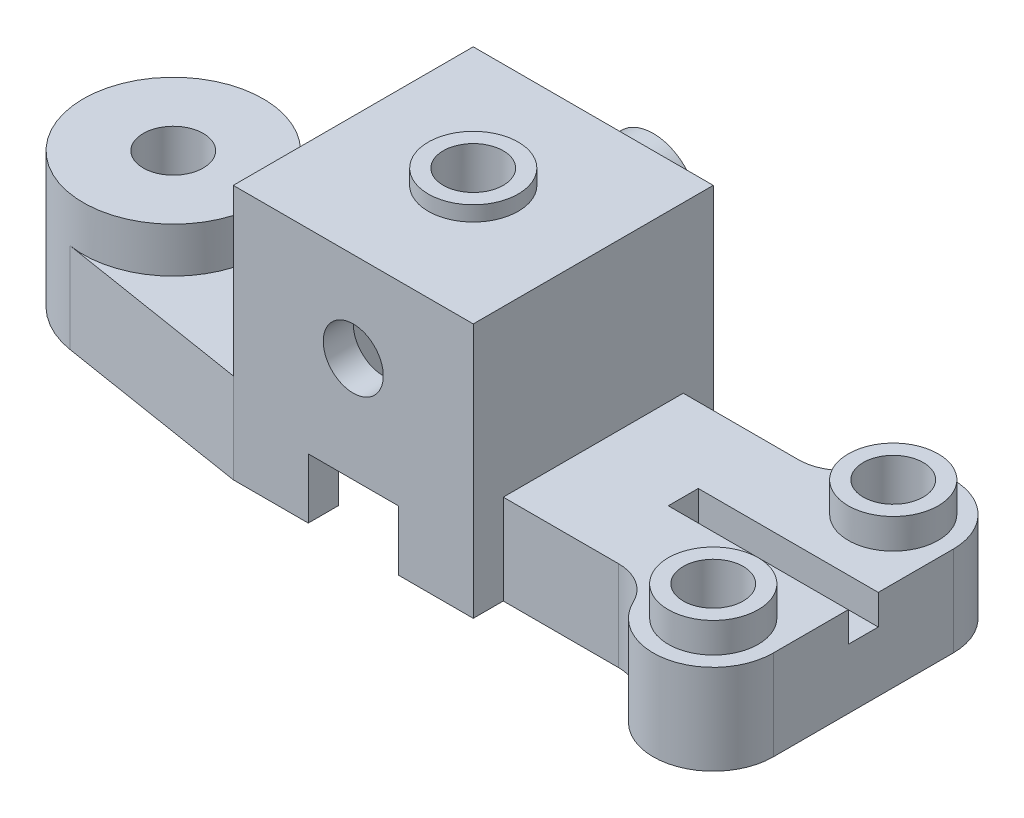
SolidWorks part; units mm, degrees
ref_plane "Front Plane" through (0, 0, 0) normal (0, 0, 1) x (1, 0, 0)
ref_plane "Top Plane" through (0, 0, 0) normal (0, 1, 0) x (1, 0, 0)
ref_plane "Right Plane" through (0, 0, 0) normal (1, 0, 0) x (0, 0, -1)
sketch "Sketch2" plane through (0, 0, 0) normal (0, 1, 0) x (1, 0, 0)
  line L1 (-40, -40) -> (40, -40)
  line L2 (-40, -40) -> (-40, 40)
  line L3 (-40, 40) -> (40, 40)
  line L4 (40, -40) -> (40, 40)
  line L5 (-40, -40) -> (40, 40) construction
  line L6 (-40, 40) -> (40, -40) construction
  point P0 (0, 0)
  dimension "D1" = 80
  dimension "D2" = 80
extrude "Boss-Extrude1" add sketch "Sketch2" along normal blind 85
sketch "Sketch3" plane through (0, 0, 40) normal (0, 0, 1) x (1, 0, 0)
  line L1 (15, -20) -> (-15, -20)
  line L2 (15, -20) -> (15, 20)
  line L3 (15, 20) -> (-15, 20)
  line L4 (-15, -20) -> (-15, 20)
  line L5 (15, -20) -> (-15, 20) construction
  line L6 (15, 20) -> (-15, -20) construction
  line L7 (-40, 0) -> (40, 0) construction
  dimension "D1" = 30
  dimension "D2" = 20
extrude "Cut-Extrude1" cut sketch "Sketch3" against normal through all
sketch "Sketch4" plane through (0, 0, -40) normal (0, 0, -1) x (-1, 0, 0)
  line L0 (15, 0) -> (40, 0) construction
  circle A0 centre (0, 55) radius 15
  point P1 (-5.7798, 40.8579)
  point P6 (0, 0)
  point P12 (0, 0)
  dimension "D1" = 30
  dimension "D2" = 55
extrude "Boss-Extrude2" add sketch "Sketch4" along normal blind 20
sketch "Sketch5" plane through (0, 85, 0) normal (0, 1, 0) x (1, 0, 0)
  circle A0 centre (0, 0) radius 15
  dimension "D1" = 30
extrude "Boss-Extrude3" add sketch "Sketch5" along normal blind 5
sketch "Sketch7" plane through (0, 0, 0) normal (0, 1, 0) x (1, 0, 0)
  circle A0 centre (-100, 0) radius 30
  circle A1 centre (0, 0) radius 15 construction
  point P4 (0, 0)
  dimension "D1" = 60
  dimension "D2" = 100
extrude "Boss-Extrude4" add sketch "Sketch7" along normal blind 45 separate body
sketch "Sketch9" plane through (0, 0, 0) normal (0, 1, 0) x (1, 0, 0)
  line L0 (-40, 40) -> (-104.7479, 29.6219)
  line L1 (0, 0) -> (-100, 0) construction
  line L2 (-40, -40) -> (-104.7479, -29.6219)
  line L3 (-40, 40) -> (-40, -40) construction
  line L4 (-40, 40) -> (-40, -40)
  circle A0 centre (-100, 0) radius 30 construction
  circle A1 centre (-100, 0) radius 30
extrude "Boss-Extrude5" add sketch "Sketch9" along normal blind 30 contours L1 L4 L0 A1 | L4 L1 A1 L2
sketch "Sketch10" plane through (0, 0, 0) normal (0, -1, 0) x (1, 0, 0)
  line L0 (-50, 28.2695) -> (-50, -28.2695)
  line L6 (-50, 28.2695) -> (-103.1653, 19.7479)
  line L7 (-40, 40) -> (-104.7479, 29.6219) construction
  line L8 (-50, -28.2695) -> (-103.1653, -19.7479)
  line L9 (-40, -40) -> (-104.7479, -29.6219) construction
  arc A0 (-104.7479, 29.6219) -> (-104.7479, -29.6219) centre (-100, 0) ccw construction
  arc A1 (-104.7479, 29.6219) -> (-104.7479, -29.6219) centre (-100, 0) ccw
  arc A2 (-103.1653, 19.7479) -> (-103.1653, -19.7479) centre (-100, 0) ccw
  point P2 (-50.4641, 28.1951)
  point P8 (0, 0)
  point P16 (0, 0)
  point P17 (0, 0)
  dimension "D4" = 20
  dimension "D1" = 10
  dimension "D2" = 10
  dimension "D3" = 10
extrude "Cut-Extrude2" cut sketch "Sketch10" against normal blind 15 contours L6 A2 L8 L0
sketch "Sketch11" plane through (0, 0, 0) normal (0, -1, 0) x (1, 0, 0)
  line L0 (15, 40) -> (40, 40) construction
  line L1 (30, -30) -> (-30, -30)
  line L2 (30, -30) -> (30, 30)
  line L3 (30, 30) -> (-30, 30)
  line L4 (-30, -30) -> (-30, 30)
  line L5 (30, -30) -> (-30, 30) construction
  line L6 (30, 30) -> (-30, -30) construction
  point P0 (0, 0)
  dimension "D1" = 10
  dimension "D2" = 10
extrude "Cut-Extrude3" cut sketch "Sketch11" against normal offset from surface (75 mm away) 10 up to face at (0, 85, 15)
sketch "Sketch12" plane through (0, 0, 0) normal (0, 1, 0) x (1, 0, 0)
  line L0 (0, 0) -> (141.2861, 0) construction
  line L1 (40, 30) -> (78.3772, 30)
  line L2 (40, -40) -> (40, 40) construction
  line L3 (40, -30) -> (78.3772, -30)
  line L4 (130, 30) -> (130, -30)
  line L5 (40, 30) -> (40, -30)
  arc A0 (130, 30) -> (91.9298, 38.5714) centre (110, 30) ccw
  arc A1 (91.9298, -38.5714) -> (130, -30) centre (110, -30) ccw
  arc A2 (78.3772, -30) -> (91.9298, -38.5714) centre (78.3772, -45) cw
  arc A3 (78.3772, 30) -> (91.9298, 38.5714) centre (78.3772, 45) ccw
  point P15 (90, -30)
  point P18 (90, 30)
  dimension "D1" = 40
  dimension "D4" = 15
  dimension "D2" = 60
  dimension "D3" = 110
extrude "Boss-Extrude6" add sketch "Sketch12" along normal blind 30
sketch "Sketch21" plane through (0, 30, 0) normal (0, 1, 0) x (1, 0, 0)
  circle A0 centre (110, 30) radius 15
  circle A1 centre (110, -30) radius 15
  dimension "D1" = 30
extrude "Boss-Extrude7" add sketch "Sketch21" along normal blind 10
hole_wizard "Ø20.0 (20) Diameter Hole1" positions "Sketch13" profile "Sketch14" hole size "Ø20.0" standard "ANSI Metric" end condition through all
sketch "Sketch13" plane through (0, 45, 0) normal (0, 1, 0) x (1, 0, 0)
  point P0 (-100, 0)
sketch "Sketch14" plane through (-100, 45, 0) normal (1, 0, 0) x (0, 0, 1)
  line L0 (0, 0) -> (0, 45)
  line L1 (0, 45) -> (10, 45)
  line L2 (10, 45) -> (10, 0)
  line L5 (10, 0) -> (0, 0)
  line L11 (0, -6.35) -> (0, 107.95) construction
  dimension "Thru Hole Dia." = 20
  dimension "Thru Hole Depth" = 45
hole_wizard "Ø20.0 (20) Diameter Hole2" positions "Sketch15" profile "Sketch16" hole size "Ø20.0" standard "ANSI Metric" end condition through all
sketch "Sketch15" plane through (0, 90, 0) normal (0, 1, 0) x (1, 0, 0)
  point P0 (0, 0)
sketch "Sketch16" plane through (0, 90, 0) normal (1, 0, 0) x (0, 0, 1)
  line L0 (0, 0) -> (0, 90)
  line L1 (0, 90) -> (10, 90)
  line L2 (10, 90) -> (10, 0)
  line L5 (10, 0) -> (0, 0)
  line L11 (0, -6.35) -> (0, 107.95) construction
  dimension "Thru Hole Dia." = 20
  dimension "Thru Hole Depth" = 90
hole_wizard "Ø20.0 (20) Diameter Hole3" positions "Sketch17" profile "Sketch18" hole size "Ø20.0" standard "ANSI Metric" end condition through all
sketch "Sketch17" plane through (0, 0, -60) normal (0, 0, -1) x (-1, 0, 0)
  circle A0 centre (0, 55) radius 15 construction
  point P0 (0, 55)
  point P4 (0, 0)
sketch "Sketch18" plane through (0, 55, -60) normal (1, 0, 0) x (0, 1, 0)
  line L0 (0, 0) -> (0, 110)
  line L1 (0, 110) -> (10, 110)
  line L2 (10, 110) -> (10, 0)
  line L5 (10, 0) -> (0, 0)
  line L11 (0, -6.35) -> (0, 107.95) construction
  dimension "Thru Hole Dia." = 20
  dimension "Thru Hole Depth" = 110
hole_wizard "CBORE for M10 Hex Head Bolt2" positions "Sketch22" profile "Sketch23" counterbore size "M10" standard "ANSI Metric" end condition through all
sketch "Sketch22" plane through (0, 40, 0) normal (0, 1, 0) x (1, 0, 0)
  point P0 (110, 30)
  point P3 (110, -30)
sketch "Sketch23" plane through (110, 40, -30) normal (1, 0, 0) x (0, 0, 1)
  line L0 (0, 0) -> (0, 40)
  line L1 (0, 40) -> (5, 40)
  line L3 (5, 40) -> (5, 15)
  line L4 (5, 15) -> (10, 15)
  line L5 (10, 15) -> (10, 0)
  line L7 (10, 0) -> (0, 0)
  line L11 (0, -6.35) -> (0, 107.95) construction
  dimension "Thru Hole Dia." = 10
  dimension "Thru Hole Depth" = 40
  dimension "C'Bore Dia." = 20
  dimension "C'Bore Depth" = 15
sketch "Sketch24" plane through (0, 0, 0) normal (0, 0, 1) x (1, 0, 0)
  line L0 (-40, 85) -> (-70, 45)
  line L2 (-40, 30) -> (-104.7479, 30) construction
  line L3 (-70, 30) -> (-70, 45) construction
  line L4 (-70, 30) -> (-40, 30)
  line L5 (-40, 30) -> (-40, 85)
  line L6 (-70, 45) -> (-71.9991, 45)
  line L7 (-70, 45) -> (-130, 45) construction
  line L8 (-71.9991, 45) -> (-71.9991, 30)
  line L9 (-71.9991, 30) -> (-70, 30)
  point P4 (-70.0689, 45)
  point P16 (-70.044, 45)
  point P17 (-70, 45.338)
  point P18 (0, 0)
  point P19 (0, 0)
  dimension "D1" = 60
  dimension "D2" = 31.9991
extrude "Boss-Extrude9" add sketch "Sketch24" along normal mid plane 10
sketch "Sketch25" plane through (130, 0, 0) normal (1, 0, 0) x (0, 0, -1)
  line L0 (-30, 30) -> (30, 30) construction
  line L1 (5, 20) -> (-5, 20)
  line L2 (5, 20) -> (5, 30)
  line L3 (5, 30) -> (-5, 30)
  line L4 (-5, 20) -> (-5, 30)
  line L5 (5, 20) -> (-5, 30) construction
  line L6 (5, 30) -> (-5, 20) construction
  point P0 (0, 25)
  point P7 (0, 0)
  dimension "D1" = 10
  dimension "D2" = 10
extrude "Cut-Extrude4" cut sketch "Sketch25" against normal blind 60
fillet "Fillet1" radius 10 4 edges at (-30, 37.5, -30) (30, 37.5, -30) (30, 37.5, 30) (-30, 37.5, 30)
